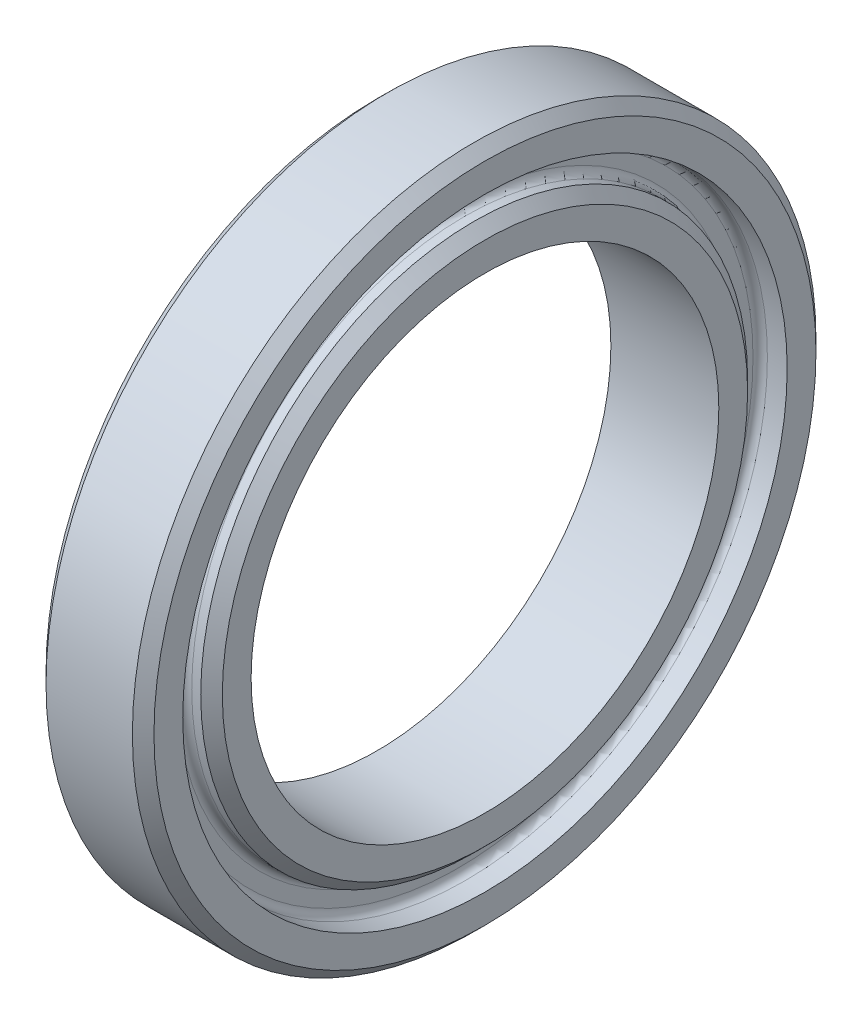
SolidWorks part; units mm, degrees
ref_plane "Płaszczyzna przednia" through (0, 0, 0) normal (0, 0, 1) x (1, 0, 0)
ref_plane "Płaszczyzna górna" through (0, 0, 0) normal (0, 1, 0) x (1, 0, 0)
ref_plane "Płaszczyzna prawa" through (0, 0, 0) normal (1, 0, 0) x (0, 0, -1)
sketch "Szkic1" plane through (0, 0, 0) normal (0, 1, 0) x (1, 0, 0)
  line L0 (0, 0) -> (0, 65) construction
  line L1 (15, 65) -> (-15, 65)
  line L2 (-15, 65) -> (-15, 76)
  line L3 (-15, 84) -> (-7.5, 84)
  line L4 (-7.5, 84) -> (-7.5, 76)
  line L5 (-7.5, 76) -> (-15, 76)
  line L6 (-15, 84) -> (-15, 95)
  line L7 (-15, 95) -> (15, 95)
  line L8 (7.5, 76) -> (15, 76)
  line L9 (15, 65) -> (15, 76)
  line L10 (7.5, 84) -> (7.5, 76)
  line L11 (15, 84) -> (7.5, 84)
  line L12 (15, 84) -> (15, 95)
  line L13 (0, 0) -> (-71.4992, 0) construction
  line L14 (-71.4992, 0) -> (-59.4917, -21.8937) construction
  point P16 (0, 95)
  dimension "D1" = 65
  dimension "D2" = 11
  dimension "D4" = 11
  dimension "D5" = 15
  dimension "D6" = 15
revolve "Obrót1" add sketch "Szkic1" angle 360 about L13
fillet "Zaokrąglenie2" radius 2 3 edges at (-7.5, 0, -84) (7.5, 0, -84) (7.5, 0, -76)
chamfer "Sfazowanie1" distance 3 angle 45 4 edges at (-15, 0, -76) (-15, 0, -95) (15, 0, -76) (15, 0, -95)
